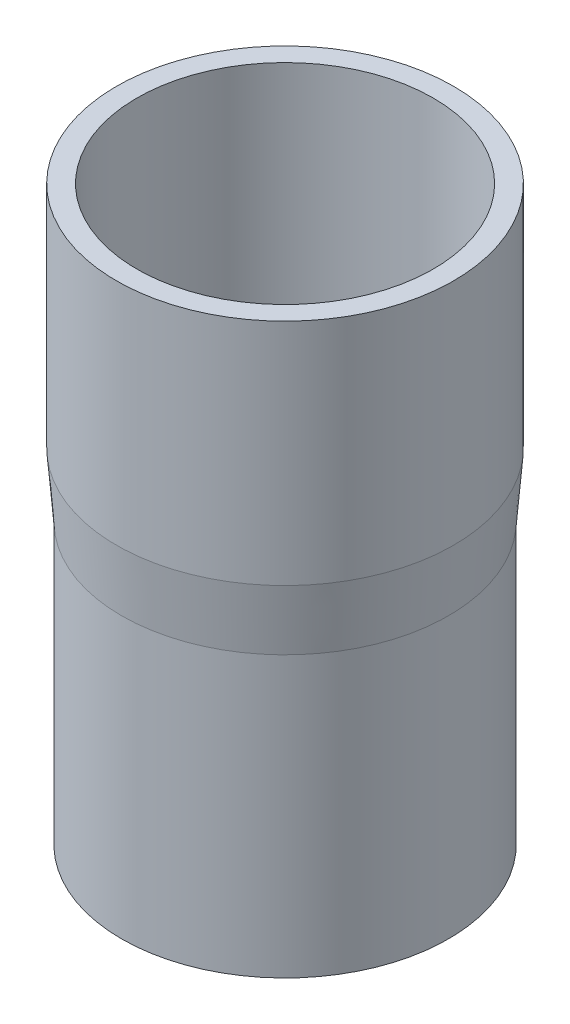
SolidWorks part; units mm, degrees
ref_plane "Front Plane" through (0, 0, 0) normal (0, 0, 1) x (1, 0, 0)
ref_plane "Top Plane" through (0, 0, 0) normal (0, 1, 0) x (1, 0, 0)
ref_plane "Right Plane" through (0, 0, 0) normal (1, 0, 0) x (0, 0, -1)
sketch "Sketch1" plane through (0, 0, 0) normal (0, 0, 1) x (1, 0, 0)
  line L0 (0, 0) -> (0, 45) construction
  line L1 (0, 0) -> (-11.25, 0)
  line L2 (-11.25, 0) -> (-12.85, 0)
  line L3 (-12.85, 0) -> (-12.85, 22)
  line L4 (-12.85, 22) -> (-13.25, 27)
  line L5 (-13.25, 27) -> (-13.25, 45)
  line L9 (-11.25, 22.0639) -> (-11.25, 0)
  line L10 (-13.25, 45) -> (-11.65, 45)
  line L11 (-11.65, 45) -> (-11.65, 27.0639)
  line L12 (0, 45) -> (-11.65, 45) construction
  line L13 (-11.65, 27.0639) -> (-11.25, 22.0639)
  dimension "D1" = 45
  dimension "D3" = 1.6
  dimension "D4" = 13.25
  dimension "D5" = 22
  dimension "D6" = 18
  dimension "D7" = 1.6
  dimension "D2" = 11.25
revolve "Revolve1" add sketch "Sketch1" angle 360 about L0
equation "\"D7@Sketch1\"=\"D3@Sketch1\""
